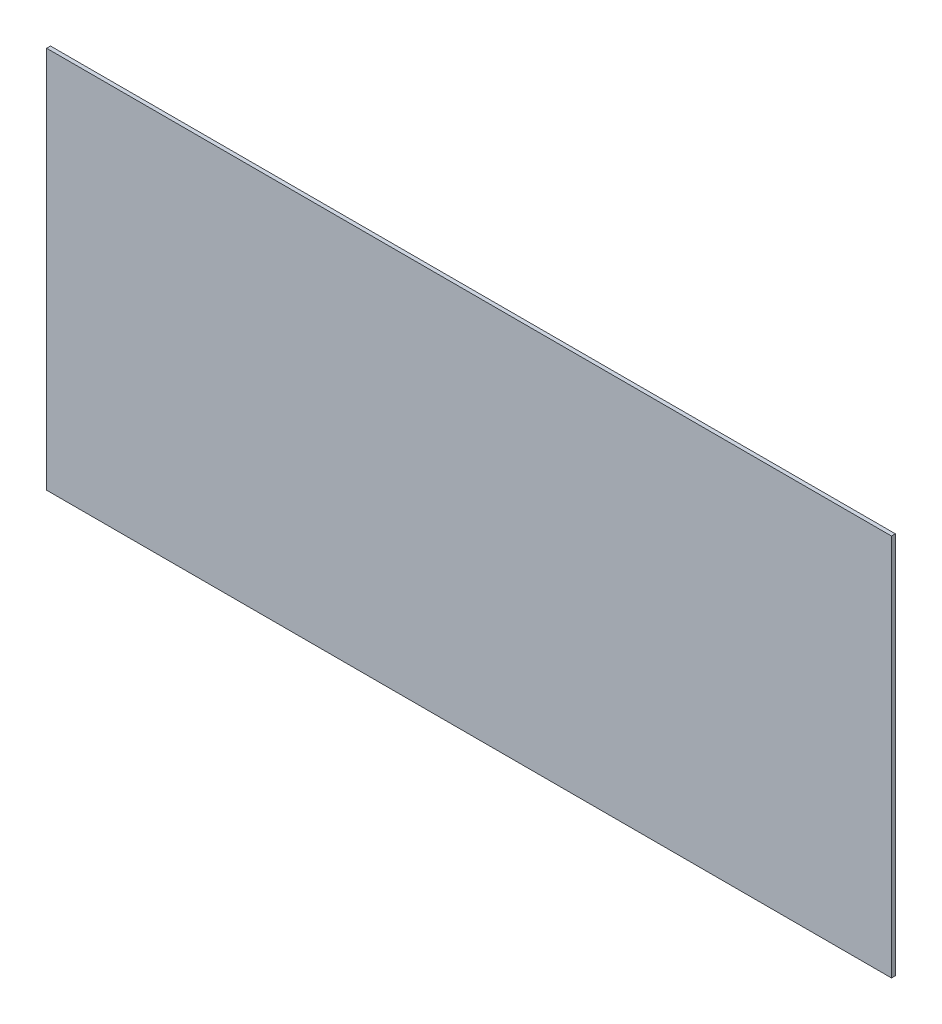
SolidWorks part; units mm, degrees
material "Custom Plastic"
ref_plane "X-Y Datum" through (0, 0, 0) normal (0, 0, 1) x (1, 0, 0)
ref_plane "X-Z Datum" through (0, 0, 0) normal (0, 1, 0) x (1, 0, 0)
ref_plane "Y-Z Datum" through (0, 0, 0) normal (1, 0, 0) x (0, 0, -1)
sketch "Sketch1" plane through (0, 0, 0) normal (0, 0, 1) x (1, 0, 0)
  line L1 (0, 0) -> (345.57, 0)
  line L2 (0, 0) -> (0, 156.55)
  line L3 (0, 156.55) -> (345.57, 156.55)
  line L4 (345.57, 0) -> (345.57, 156.55)
  dimension "D2" = 156.55
  dimension "D3" = 345.57
extrude "Boss-Extrude1" add sketch "Sketch1" along normal blind 1.5875
